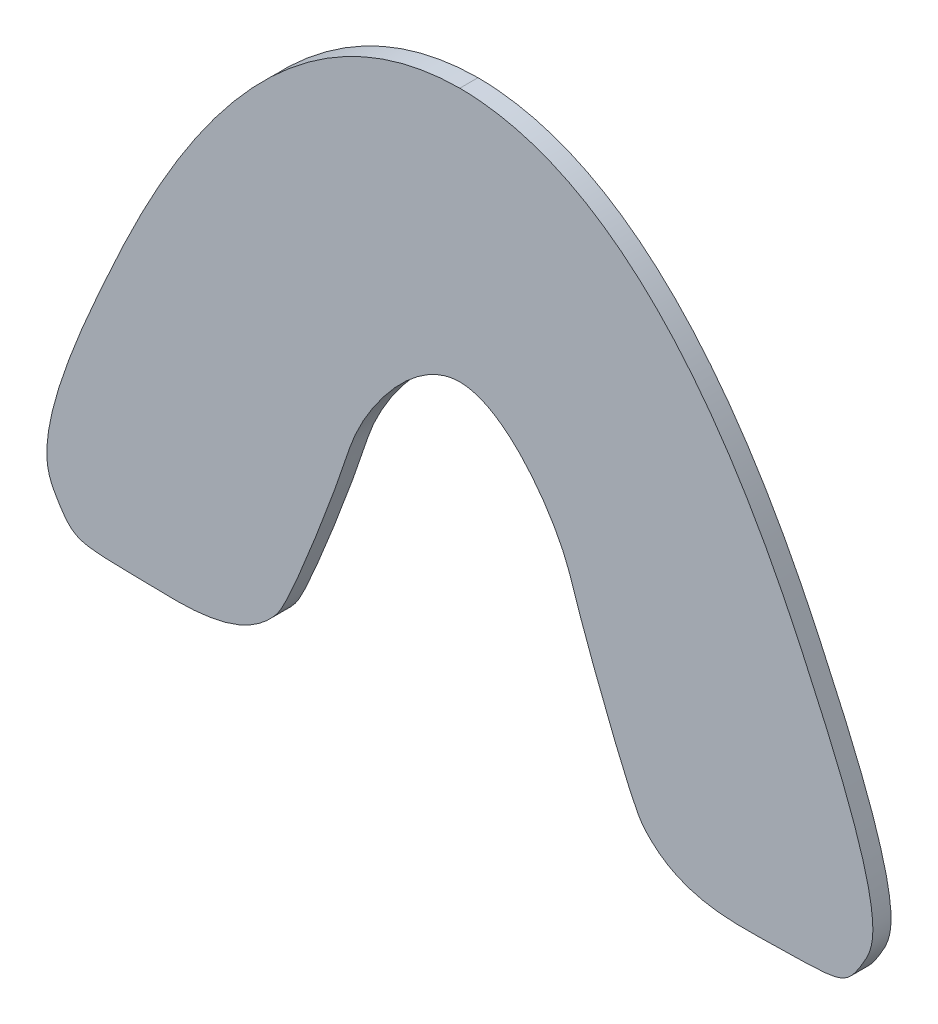
SolidWorks part; units mm, degrees
ref_plane "Front Plane" through (0, 0, 0) normal (0, 0, 1) x (1, 0, 0)
ref_plane "Top Plane" through (0, 0, 0) normal (0, 1, 0) x (1, 0, 0)
ref_plane "Right Plane" through (0, 0, 0) normal (1, 0, 0) x (0, 0, -1)
sketch "Esboço1" plane through (0, 0, 0) normal (0, 0, 1) x (1, 0, 0)
  line L0 (-35, 0) -> (40, 0) construction
  line L1 (0, -25) -> (0, 40) construction
  line L2 (-25, -25) -> (25, -25) construction
  line L3 (-40, -20) -> (45, -20) construction
  spline S0 degree 3 poles (0, 12) (4.7616, 12) (10.8518, 3.8365) (13.6515, -5.2811) (18.9456, -18.7639) (21.3142, -21.6454) (24.9322, -24.6832) (41.7578, -24.1852) (42.4848, -24.5675) (46.7345, -17.1188) (42.8674, -6.4279) (36.4301, 8.0373) (21.5645, 39.8588) (0, 40) knots 0.303894 0.303894 0.303894 0.303894 0.349477 0.361676 0.418753 0.434216 0.500843 0.520949 0.615173 0.635302 0.70211 0.719804 0.803894 0.803894 0.803894 0.803894
  spline S1 degree 3 poles (0, 12) (-4.7616, 12) (-10.8518, 3.8365) (-13.6515, -5.2811) (-18.9456, -18.7639) (-21.3142, -21.6454) (-24.9322, -24.6832) (-41.7578, -24.1852) (-42.4848, -24.5675) (-46.7345, -17.1188) (-42.8674, -6.4279) (-36.4301, 8.0373) (-21.5645, 39.8588) (0, 40) knots 0.303894 0.303894 0.303894 0.303894 0.349477 0.361676 0.418753 0.434216 0.500843 0.520949 0.615173 0.635302 0.70211 0.719804 0.803894 0.803894 0.803894 0.803894
  point P9 (0, 0)
  point P10 (-15, -20)
  point P11 (0, -20)
  point P12 (20, -20)
  point P13 (12, 0)
  point P14 (-10, 0)
  point P15 (0, 12)
  dimension "D1" = 25
  dimension "D2" = 25
  dimension "D3" = 45
  dimension "D4" = 40
  dimension "D5" = 40
  dimension "D6" = 35
  dimension "D7" = 20
  dimension "D8" = 25
  dimension "D9" = 40
  dimension "D10" = 12
  dimension "D11" = 12
  dimension "D12" = 10
  dimension "D13" = 20
  dimension "D14" = 15
extrude "Ressalto-extrusão1" add sketch "Esboço1" along normal blind 2
